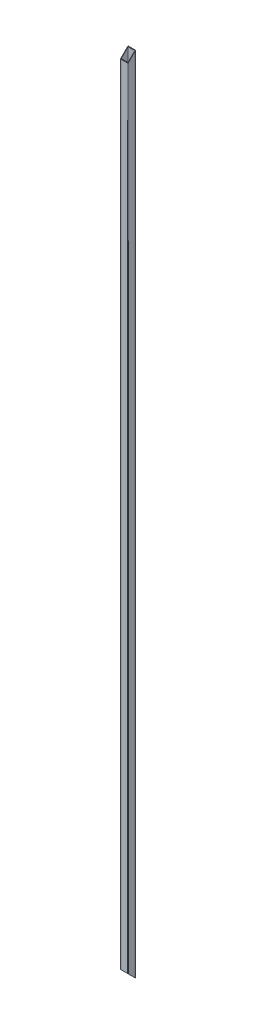
SolidWorks part; units mm, degrees
ref_plane "Спереди" through (0, 0, 0) normal (0, 0, 1) x (1, 0, 0)
ref_plane "Сверху" through (0, 0, 0) normal (0, 1, 0) x (1, 0, 0)
ref_plane "Справа" through (0, 0, 0) normal (1, 0, 0) x (0, 0, -1)
sketch "Эскиз2" plane through (0, 0, 0) normal (0, 1, 0) x (1, 0, 0)
  line L1 (-18, 20) -> (18, 20)
  line L2 (-20, 18) -> (-20, -18)
  line L3 (-18, -20) -> (18, -20)
  line L4 (20, 18) -> (20, -18)
  line L5 (-20, 20) -> (20, -20) construction
  line L6 (-20, -20) -> (20, 20) construction
  line L7 (16, -18) -> (-16, -18)
  line L8 (18, -16) -> (18, 16)
  line L9 (16, 18) -> (-16, 18)
  line L10 (-18, -16) -> (-18, 16)
  line L11 (18, -18) -> (-18, 18) construction
  line L12 (18, 18) -> (-18, -18) construction
  arc A0 (16, -18) -> (18, -16) centre (16, -16) ccw
  arc A1 (18, -20) -> (20, -18) centre (18, -18) ccw
  arc A2 (-20, -18) -> (-18, -20) centre (-18, -18) ccw
  arc A3 (-16, -18) -> (-18, -16) centre (-16, -16) cw
  arc A4 (18, 20) -> (20, 18) centre (18, 18) cw
  arc A5 (18, 16) -> (16, 18) centre (16, 16) ccw
  arc A6 (-18, 20) -> (-20, 18) centre (-18, 18) ccw
  arc A7 (-16, 18) -> (-18, 16) centre (-16, 16) ccw
  point P0 (0, 0)
  point P6 (0, 0)
  dimension "D5" = 2
  dimension "D1" = 40
  dimension "D2" = 40
  dimension "D3" = 2
  dimension "D4" = 2
extrude "Бобышка-Вытянуть1" add sketch "Эскиз2" along normal blind 4240
sketch "Эскиз3" plane through (20, 0, 0) normal (1, 0, 0) x (0, 0, -1)
  line L0 (20, 4240) -> (-20, 4240)
  line L1 (-20, 4240) -> (-20, 4200)
  line L2 (-20, 4240) -> (-20, 0) construction
  line L3 (-20, 4200) -> (20, 4240)
  line L4 (20, 0) -> (-20, 0)
  line L5 (-20, 0) -> (-20, 40)
  line L6 (-20, 40) -> (20, 0)
  dimension "D1" = 45
  dimension "D2" = 45
extrude "Вырез-Вытянуть1" cut sketch "Эскиз3" against normal through all
